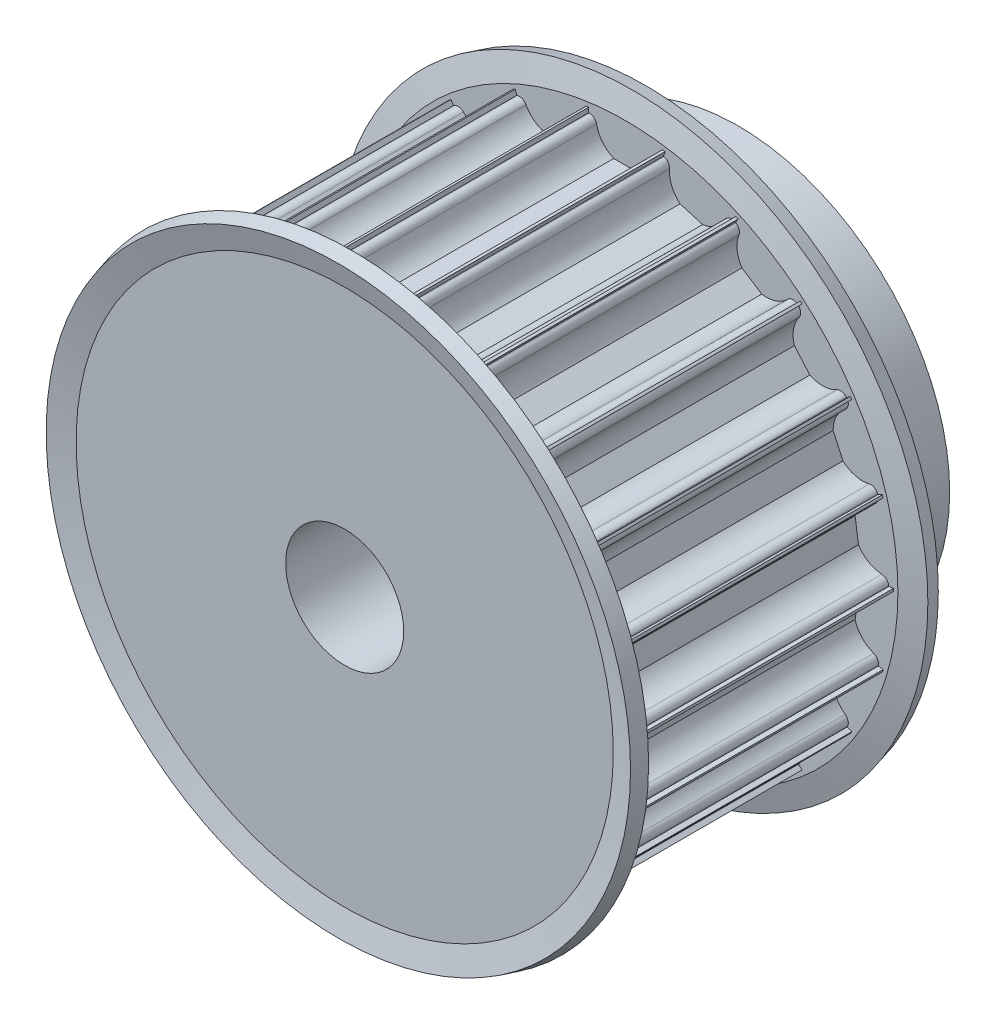
SolidWorks part; units mm, degrees
ref_plane "Front Plane" through (0, 0, 0) normal (0, 0, 1) x (1, 0, 0)
ref_plane "Top Plane" through (0, 0, 0) normal (0, 1, 0) x (1, 0, 0)
ref_plane "Right Plane" through (0, 0, 0) normal (1, 0, 0) x (0, 0, -1)
sketch "Sketch1" plane through (0, 0, 0) normal (1, 0, 0) x (0, 0, -1)
  line L0 (0, 0) -> (37.7091, 0) construction
  line L1 (0, 6) -> (0, 27.25)
  line L2 (0, 27.25) -> (30, 27.25)
  line L3 (30, 27.25) -> (30, 21.5)
  line L4 (30, 21.5) -> (40, 21.5)
  line L5 (40, 21.5) -> (40, 6)
  line L6 (40, 6) -> (0, 6)
  dimension "D1" = 27.25
  dimension "D2" = 6
  dimension "D3" = 30
  dimension "D4" = 10
  dimension "D5" = 15.5
revolve "Revolve1" add sketch "Sketch1" angle 360 about L0
sketch "Sketch2" plane through (0, 0, 0) normal (0, 0, 1) x (1, 0, 0)
  line L0 (-3.6742, 26.5) -> (-3.75, 26.5)
  line L1 (-3.75, 26.5) -> (-3.75, 28.5)
  line L2 (-3.75, 28.5) -> (3.75, 28.5)
  line L3 (3.75, 28.5) -> (3.75, 26.5)
  line L4 (3.75, 26.5) -> (3.6742, 26.5)
  line L5 (-1.199, 23.75) -> (1.199, 23.75)
  arc A0 (2.9394, 25.9) -> (1.199, 23.75) centre (0, 26.5) cw
  arc A1 (2.9394, 25.9) -> (3.6742, 26.5) centre (3.6742, 25.75) cw
  arc A2 (-2.9394, 25.9) -> (-3.6742, 26.5) centre (-3.6742, 25.75) ccw
  arc A3 (-1.199, 23.75) -> (-2.9394, 25.9) centre (0, 26.5) cw
  dimension "D1" = 3
  dimension "D5" = 0.75
  dimension "D2" = 26.5
  dimension "D3" = 7.5
  dimension "D4" = 2
  dimension "D6" = 2.75
extrude "Cut-Extrude1" cut sketch "Sketch2" against normal up to next
pattern_circular "CirPattern1" count 22 over 360 about axis through (0, 0, 0) along (0, 0, 1) of "Cut-Extrude1"
sketch "Sketch3" plane through (0, 0, 0) normal (1, 0, 0) x (0, 0, -1)
  line L0 (15, 26.9539) -> (15, 10.9567) construction
  line L1 (30, 26.9539) -> (0, 26.9539) construction
  line L2 (30, 10.9567) -> (0, 10.9567) construction
  line L3 (30, 21.5) -> (30, 27.3018)
  line L4 (30, 27.3018) -> (30.6431, 29.7018)
  line L5 (30.6431, 29.7018) -> (29.1942, 30.09)
  line L6 (29.1942, 30.09) -> (28.5511, 27.69)
  line L7 (28.5511, 27.69) -> (28.5511, 21.5)
  line L8 (28.5511, 21.5) -> (30, 21.5)
  line L9 (1.4489, 21.5) -> (0, 21.5)
  line L10 (0, 21.5) -> (0, 27.3018)
  line L11 (0, 27.3018) -> (-0.6431, 29.7018)
  line L12 (-0.6431, 29.7018) -> (0.8058, 30.09)
  line L13 (0.8058, 30.09) -> (1.4489, 27.69)
  line L14 (1.4489, 27.69) -> (1.4489, 21.5)
  line L15 (0, 0) -> (26.6899, 0) construction
  dimension "D1" = 15
  dimension "D2" = 1.5
  dimension "D3" = 6.19
  dimension "D4" = 2.4
revolve "Revolve2" add sketch "Sketch3" angle 360 about L15
